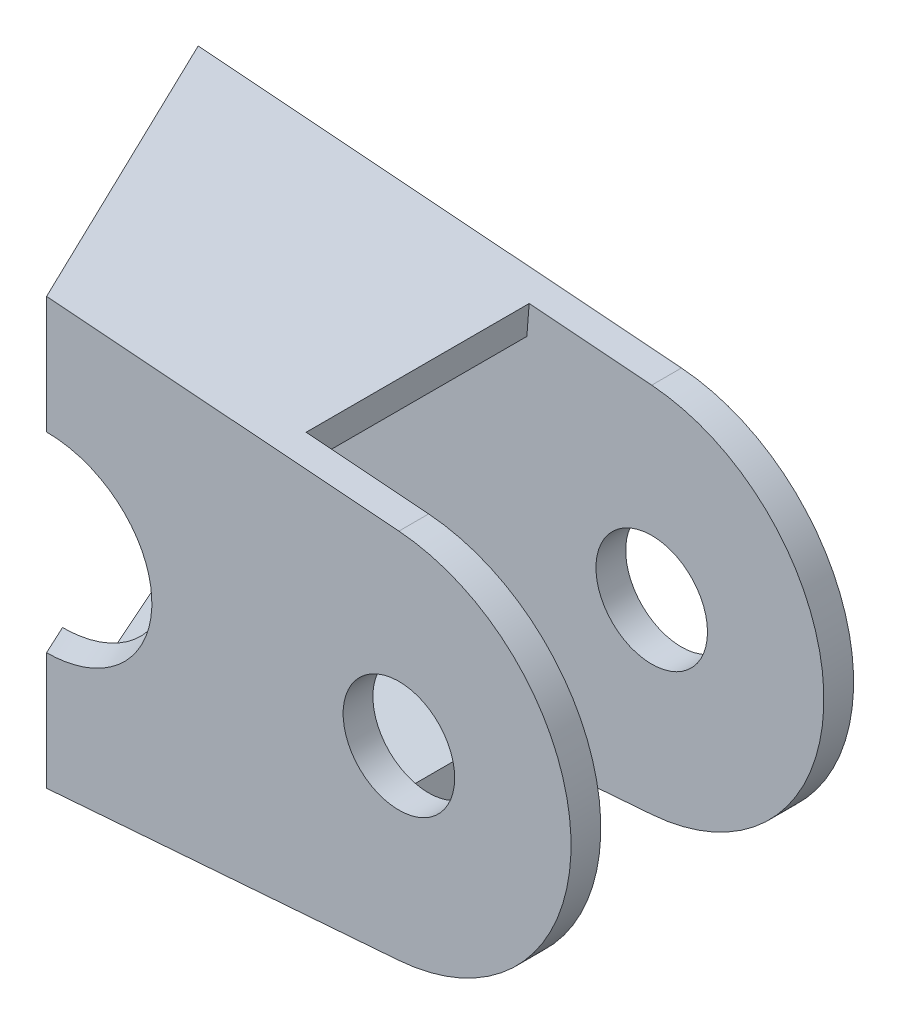
SolidWorks part; units mm, degrees
ref_plane "Front Plane" through (0, 0, 0) normal (0, 0, 1) x (1, 0, 0)
ref_plane "Top Plane" through (0, 0, 0) normal (0, 1, 0) x (1, 0, 0)
ref_plane "Right Plane" through (0, 0, 0) normal (1, 0, 0) x (0, 0, -1)
sketch3d "3DSketch2" plane through (0, 0, 0) normal (0, 0, 1) x (1, 0, 0)
  dimension "D1" = 15
sketch "Sketch2" plane through (0, 0, 15) normal (0, 0, 1) x (1, 0, 0)
  line L0 (0, 0) -> (-65, 0) construction
  line L1 (0, 0) -> (0, -39.5077) construction
  line L2 (-65, 30) -> (-65, -30)
  line L3 (-65, -30) -> (0, -25)
  line L4 (-65, 30) -> (0, 25)
  circle A0 centre (0, 0) radius 7.5
  arc A1 (0, 25) -> (0, -25) centre (-1.9231, 0) cw
  point P6 (-65, 0)
  dimension "D1" = 15
  dimension "D2" = 65
  dimension "D3" = 60
  dimension "D4" = 25
extrude "Boss-Extrude2" add sketch "Sketch2" along normal blind 4
mirror "Mirror2" about plane through (0, 0, 0) normal (0, 0, 1) of bodies 102
sketch3d "3DSketch3"
  line L0 (-65, 30, 19) -> (-65, -30, 19) construction
  line L1 (-47.3852, 28.645, 19) -> (-47.3852, -28.645, 19)
  line L2 (-65, 30, -19) -> (-65, -30, -19) construction
  line L3 (-65, 0, 19) -> (-47.3852, 0, 19) construction
  line L4 (-65, 0, -19) -> (-47.3852, 0, 19)
  line L5 (-65, 0, -19) -> (-65, 0, 19) construction
  line L6 (-40.4409, 0, 33.9807) -> (-29.8127, 5.2814, 29.0541) construction
  line L7 (-65, 0, -19) -> (-40.4409, 0, 33.9807)
  line L8 (-65, -30, 19) -> (0, -25, 19) construction
  line L9 (-47.3852, 28.645, 19) -> (-65, 30, 19)
  line L10 (0, 25, 19) -> (-65, 30, 19) construction
  line L11 (-65, 30, 19) -> (-65, -30, 19)
  line L12 (-65, -30, 19) -> (-47.3852, -28.645, 19)
  line L13 (-40.4409, 30.3168, 33.9807) -> (-40.4409, 12.85, 33.9807)
  line L14 (-40.4409, 30.3168, 33.9807) -> (-82.431, 39.1749, 53.4452)
  line L15 (-82.431, 39.1749, 53.4452) -> (-94.6589, -31.244, 59.1134)
  line L16 (-94.6589, -31.244, 59.1134) -> (-40.4409, -30.3168, 33.9807)
  line L17 (-40.4409, -12.85, 33.9807) -> (-40.4409, -30.3168, 33.9807)
  arc A0 (-40.4409, -12.85, 33.9807) -> (-40.4409, 12.85, 33.9807) centre (-40.4409, 0, 33.9807) ccw
  point P0 (-65, 0, 19)
  point P4 (-65, 0, -19)
  point P11 (-35.0367, 0, 45.6391)
  point P17 (-47.3852, 0, 19)
  point P25 (-40.4409, 0, 33.9807)
  dimension "D2" = 25.7
  dimension "D1" = 24.87
extrude "Cut-Extrude1" cut sketch "3DSketch3" along direction (0.4206, 0, 0.9073) on the side against the normal blind 67 contours A0 L13 L14 L15 L16 L17
sketch "Sketch3" plane through (1.9118, 24.8529, 0) normal (0.0767, 0.9971, 0) x (0.9971, -0.0767, 0)
  line L0 (-65.2498, 15) -> (-51.3022, -15)
  line L1 (-51.3022, -15) -> (-18.45, -15)
  line L2 (-18.45, -15) -> (-18.45, 15)
  line L3 (-1.9174, 15) -> (-65.2498, 15) construction
  line L4 (-18.45, 15) -> (-65.2498, 15)
extrude "Boss-Extrude3" add sketch "Sketch3" against normal blind 4
mirror "Mirror3" about plane through (0, 0, 0) normal (0, 1, 0) of "Boss-Extrude3"
